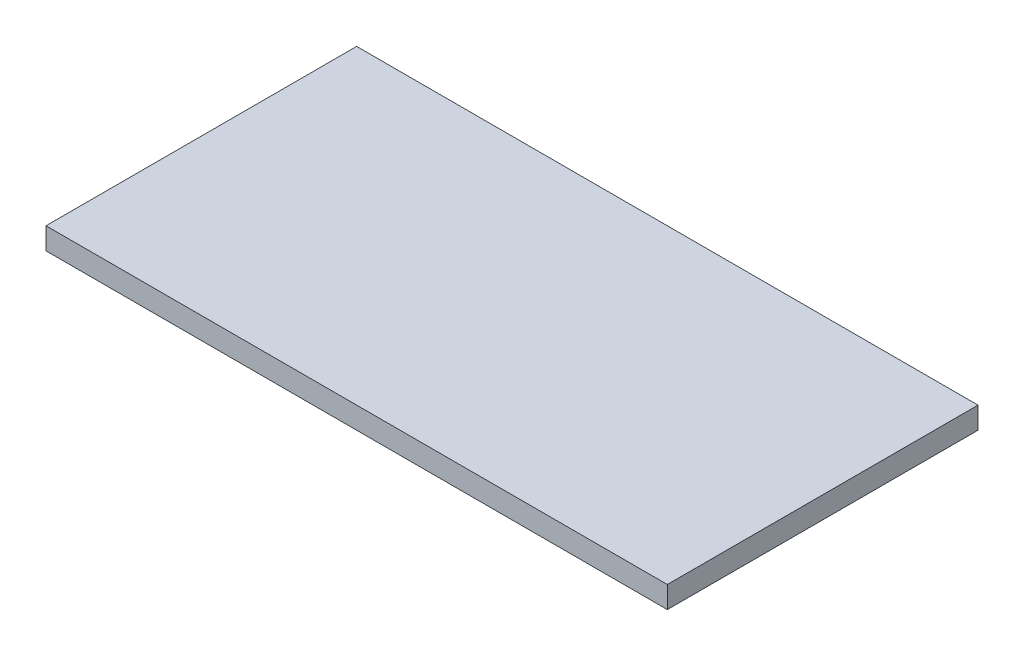
SolidWorks part; units mm, degrees
ref_plane "Front Plane" through (0, 0, 0) normal (0, 0, 1) x (1, 0, 0)
ref_plane "Top Plane" through (0, 0, 0) normal (0, 1, 0) x (1, 0, 0)
ref_plane "Right Plane" through (0, 0, 0) normal (1, 0, 0) x (0, 0, -1)
sketch "Sketch1" plane through (0, 0, 0) normal (0, 1, 0) x (1, 0, 0)
  line L1 (-10, -5) -> (10, -5)
  line L2 (-10, -5) -> (-10, 5)
  line L3 (-10, 5) -> (10, 5)
  line L4 (10, -5) -> (10, 5)
  line L5 (-10, -5) -> (10, 5) construction
  line L6 (-10, 5) -> (10, -5) construction
  point P0 (0, 0)
  dimension "D1" = 10
  dimension "D2" = 20
extrude "Boss-Extrude1" add sketch "Sketch1" along normal blind 0.7
